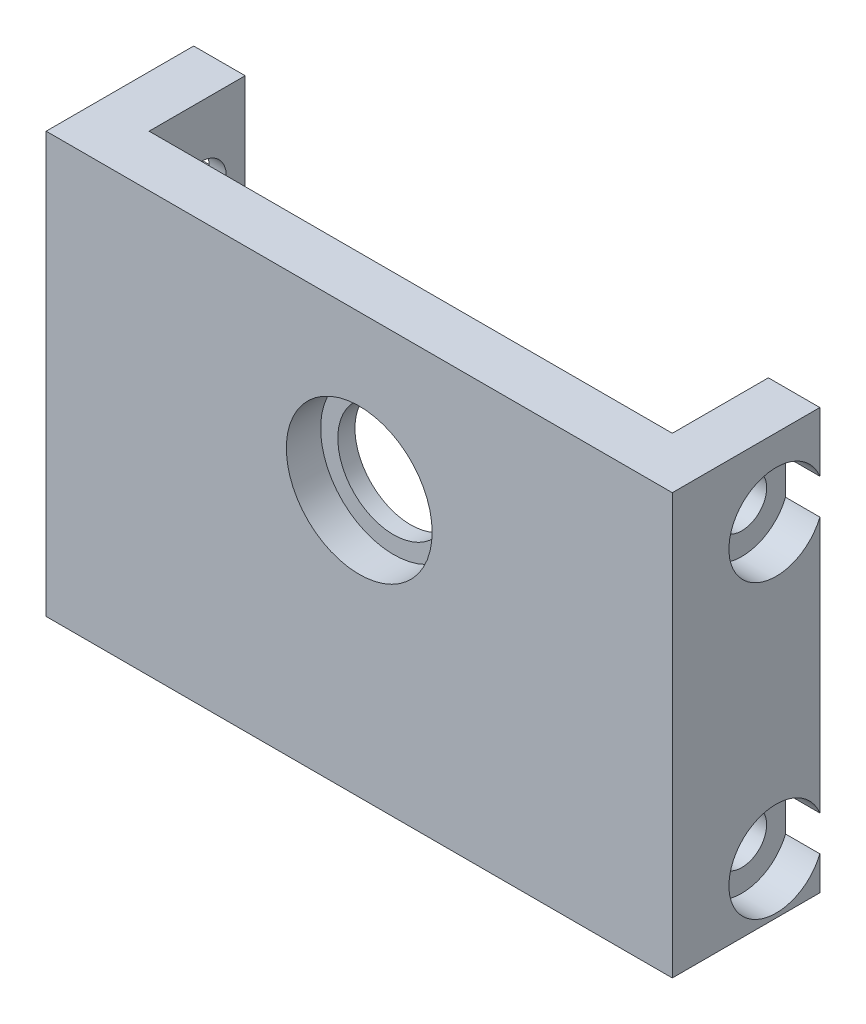
SolidWorks part; units mm, degrees
ref_plane "Plano frontal" through (0, 0, 0) normal (0, 0, 1) x (1, 0, 0)
ref_plane "Plano superior" through (0, 0, 0) normal (0, 1, 0) x (1, 0, 0)
ref_plane "Plano direito" through (0, 0, 0) normal (1, 0, 0) x (0, 0, -1)
other "Centro da massa"
sketch "Esboço2" plane through (0, 0, 0) normal (0, 0, 1) x (1, 0, 0)
  line L0 (2.5, -18.5) -> (4.5, -18.5) construction
  line L1 (-0.25, 3) -> (30.25, 3)
  line L2 (-0.25, 3) -> (-0.25, -21.5)
  line L3 (-0.25, -21.5) -> (30.25, -21.5)
  line L4 (30.25, 3) -> (30.25, -21.5)
  line L7 (0, -38.6) -> (0, 0) construction
  line L9 (-0.25, -1.1531) -> (0, -1.1531) construction
  line L11 (30, -1.6003) -> (30.25, -1.6003) construction
  line L12 (30, -38.6) -> (30, 0) construction
  arc A0 (18.9245, -1.4615) -> (9.4709, -3.67) centre (15, -6) ccw construction
  dimension "D1" = 9
  dimension "D2" = 0.25
  dimension "D3" = 3
extrude "Ressalto-extrusão1" add sketch "Esboço2" along normal blind 3 from offset 0.25
ref_plane "Plano1" through (15, 0, 0) normal (-1, 0, 0) x (0, 0, 1)
sketch "Esboço3" plane through (-0.25, 0, 0) normal (-1, 0, 0) x (0, 0, 1)
  line L0 (3.25, -21.5) -> (0.25, -21.5) construction
  line L1 (3.25, 3) -> (-5.35, 3)
  line L2 (3.25, 3) -> (3.25, -21.5)
  line L3 (3.25, -21.5) -> (-5.35, -21.5)
  line L4 (-5.35, 3) -> (-5.35, -21.5)
  dimension "D1" = 0.25
extrude "Ressalto-extrusão2" add sketch "Esboço3" along normal blind 3
mirror "Espelhar1" about plane through (15, 0, 0) normal (-1, 0, 0) of "Ressalto-extrusão2"
sketch "Esboço5" plane through (0, 0, 3.25) normal (0, 0, 1) x (1, 0, 0)
  circle A2 centre (15, -6) radius 4.25
  circle A3 centre (15, -6) radius 4 construction
  dimension "D1" = 0.25
extrude "Corte-extrusão1" cut sketch "Esboço5" against normal offset from surface (2 mm away) 1 up to face at (15, -9.25, 0.25)
sketch "Esboço12" plane through (0, 0, 1.25) normal (0, 0, 1) x (1, 0, 0)
  circle A0 centre (15, -6) radius 3.25 construction
  circle A1 centre (15, -6) radius 3.25
extrude "Corte-extrusão3" cut sketch "Esboço12" against normal through all
ref_plane "Plane1" through (15, 0, 0) normal (-1, 0, 0) x (0, 0, 1)
hole_wizard "CBORE for M2.5 SHCS1" positions "Sketch3" profile "Sketch4" counterbore size "M2.5" standard "ANSI Metric"
sketch "Sketch3" plane through (-3.25, 0, 0) normal (-1, 0, 0) x (0, 0, 1)
  circle A0 centre (-2.8, -1.5) radius 1.35 construction
  circle A1 centre (-2.8, -18.5) radius 1.35 construction
  point P0 (-2.8, -1.5)
  point P2 (-2.8, -18.5)
sketch "Sketch4" plane through (-3.25, -1.5, -2.8) normal (0, 1, 0) x (0, 0, 1)
  line L0 (0, 0) -> (0, 3)
  line L1 (0, 3) -> (1.45, 3)
  line L3 (1.45, 3) -> (1.45, 2)
  line L4 (1.45, 2) -> (2.75, 2)
  line L5 (2.75, 2) -> (2.75, 0)
  line L7 (2.75, 0) -> (0, 0)
  line L11 (0, -6.35) -> (0, 107.95) construction
  dimension "Thru Hole Dia." = 2.9
  dimension "Thru Hole Depth" = 3
  dimension "C'Bore Dia." = 5.5
  dimension "C'Bore Depth" = 2
mirror "Mirror1" about plane through (15, 0, 0) normal (-1, 0, 0) of "CBORE for M2.5 SHCS1"
